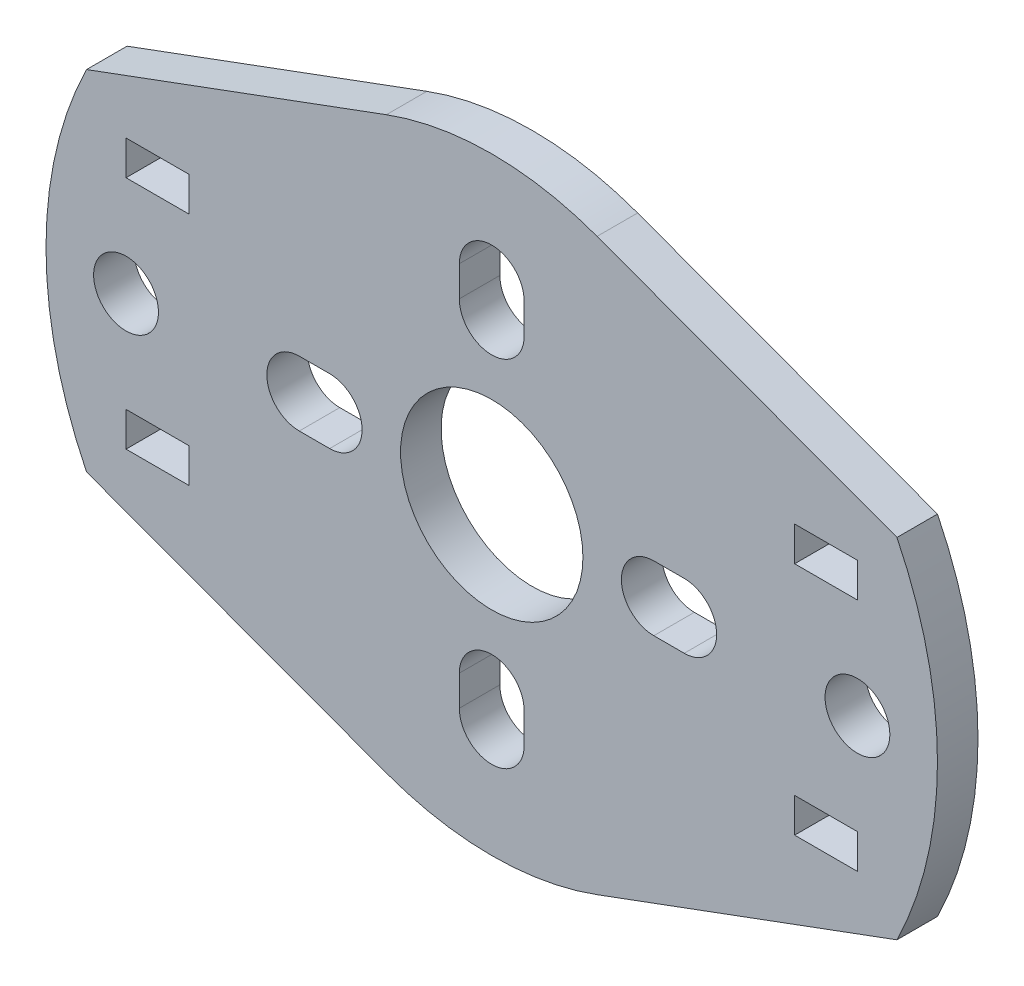
SolidWorks part; units mm, degrees
material "Thornel VCB-20 Carbon Cloth"
ref_plane "Front Plane" through (0, 0, 0) normal (0, 0, 1) x (1, 0, 0)
ref_plane "Top Plane" through (0, 0, 0) normal (0, 1, 0) x (1, 0, 0)
ref_plane "Right Plane" through (0, 0, 0) normal (1, 0, 0) x (0, 0, -1)
sketch "Sketch1" plane through (0, 0, 0) normal (0, 0, 1) x (1, 0, 0)
  line L0 (-105.2, 14.0698) -> (-120, 8.6)
  line L1 (-120, 8.6) -> (-120, -8.6)
  line L2 (-120, 0) -> (-80, 0) construction
  line L3 (-80, -8.6) -> (-80, 8.6)
  line L4 (-80, 8.6) -> (-94.8, 14.0698)
  line L5 (-80, -8.6) -> (-94.8, -14.0698)
  line L6 (-105.2, -14.0698) -> (-120, -8.6)
  line L15 (-114.95, 6.65) -> (-118.05, 6.65)
  line L16 (-118.05, 6.65) -> (-118.05, 4.95)
  line L17 (-118.05, 4.95) -> (-114.95, 4.95)
  line L18 (-114.95, 4.95) -> (-114.95, 6.65)
  line L19 (-114.95, 6.65) -> (-118.05, 6.65)
  line L20 (-118.05, 6.65) -> (-118.05, 4.95)
  line L21 (-118.05, 4.95) -> (-114.95, 4.95)
  line L22 (-114.95, 4.95) -> (-114.95, 6.65)
  line L27 (-81.95, 6.65) -> (-85.05, 6.65)
  line L28 (-85.05, 6.65) -> (-85.05, 4.95)
  line L29 (-85.05, 4.95) -> (-81.95, 4.95)
  line L30 (-81.95, 4.95) -> (-81.95, 6.65)
  line L31 (-81.95, 6.65) -> (-85.05, 6.65)
  line L32 (-85.05, 6.65) -> (-85.05, 4.95)
  line L33 (-85.05, 4.95) -> (-81.95, 4.95)
  line L34 (-81.95, 4.95) -> (-81.95, 6.65)
  line L39 (-114.95, -4.95) -> (-118.05, -4.95)
  line L40 (-118.05, -4.95) -> (-118.05, -6.65)
  line L41 (-118.05, -6.65) -> (-114.95, -6.65)
  line L42 (-114.95, -6.65) -> (-114.95, -4.95)
  line L43 (-114.95, -4.95) -> (-118.05, -4.95)
  line L44 (-118.05, -4.95) -> (-118.05, -6.65)
  line L45 (-118.05, -6.65) -> (-114.95, -6.65)
  line L46 (-114.95, -6.65) -> (-114.95, -4.95)
  line L51 (-81.95, -4.95) -> (-85.05, -4.95)
  line L52 (-85.05, -4.95) -> (-85.05, -6.65)
  line L53 (-85.05, -6.65) -> (-81.95, -6.65)
  line L54 (-81.95, -6.65) -> (-81.95, -4.95)
  line L55 (-81.95, -4.95) -> (-85.05, -4.95)
  line L56 (-85.05, -4.95) -> (-85.05, -6.65)
  line L57 (-85.05, -6.65) -> (-81.95, -6.65)
  line L58 (-81.95, -6.65) -> (-81.95, -4.95)
  circle A0 centre (-100, 0) radius 15 construction
  arc A1 (-105.2, -14.0698) -> (-94.8, -14.0698) centre (-100, 0) ccw
  arc A2 (-94.8, 14.0698) -> (-105.2, 14.0698) centre (-100, 0) ccw
  dimension "D1" = 2
  dimension "D2" = 2
  dimension "D3" = 2
  dimension "D4" = 0.05
  dimension "D5" = 0.05
  dimension "D6" = 0.05
  dimension "D7" = 0.05
extrude "Boss-Extrude1" add sketch "Sketch1" along normal blind 2
sketch "Sketch2" plane through (0, 0, 2) normal (0, 0, 1) x (1, 0, 0)
  line L0 (-108, 0) -> (-109.5, 0) construction
  line L1 (-108, -1.6) -> (-109.5, -1.6)
  line L2 (-108, 1.6) -> (-109.5, 1.6)
  line L4 (-100, 8) -> (-100, 9.5) construction
  line L5 (-101.6, 8) -> (-101.6, 9.5)
  line L6 (-98.4, 8) -> (-98.4, 9.5)
  line L7 (-92, 0) -> (-90.5, 0) construction
  line L8 (-92, 1.6) -> (-90.5, 1.6)
  line L9 (-92, -1.6) -> (-90.5, -1.6)
  line L10 (-100, -8) -> (-100, -9.5) construction
  line L11 (-98.4, -8) -> (-98.4, -9.5)
  line L12 (-101.6, -8) -> (-101.6, -9.5)
  circle A0 centre (-100, 0) radius 4.5
  arc A1 (-108, -1.6) -> (-108, 1.6) centre (-108, 0) ccw
  arc A2 (-109.5, 1.6) -> (-109.5, -1.6) centre (-109.5, 0) ccw
  arc A3 (-101.6, 8) -> (-98.4, 8) centre (-100, 8) ccw
  arc A4 (-98.4, 9.5) -> (-101.6, 9.5) centre (-100, 9.5) ccw
  arc A5 (-92, 1.6) -> (-92, -1.6) centre (-92, 0) ccw
  arc A6 (-90.5, -1.6) -> (-90.5, 1.6) centre (-90.5, 0) ccw
  arc A7 (-98.4, -8) -> (-101.6, -8) centre (-100, -8) ccw
  arc A8 (-101.6, -9.5) -> (-98.4, -9.5) centre (-100, -9.5) ccw
  point P5 (-108.75, 0)
  point P16 (-100, 8.75)
  point P23 (-91.25, 0)
  point P30 (-100, -8.75)
  point P35 (-100, 0)
  dimension "D2" = 9
  dimension "D4" = 16
  dimension "D5" = 19
  dimension "D6" = 3.2
  dimension "D3" = 4
extrude "Cut-Extrude1" cut sketch "Sketch2" against normal up to next
sketch "Sketch5" plane through (0, 0, 2) normal (0, 0, 1) x (1, 0, 0)
  line L0 (-120, 8.6) -> (-120, -8.6)
  line L1 (-80, 8.6) -> (-80, -8.6)
  arc A0 (-120, -8.6) -> (-120, 8.6) centre (-102.51, 0) cw
  arc A1 (-80, 8.6) -> (-80, -8.6) centre (-97.49, 0) cw
  point P5 (-122, 0)
  dimension "D1" = 2
extrude "Boss-Extrude2" add sketch "Sketch5" against normal up to vertex (2 mm away) up to point (-98.4, 8, 0)
sketch "Sketch3" plane through (0, 0, 2) normal (0, 0, 1) x (1, 0, 0)
  line L0 (-118.05, 4.95) -> (-118.05, -4.95) construction
  line L3 (-81.95, 4.95) -> (-81.95, -4.95) construction
  line L7 (-85.05, 4.95) -> (-81.95, 4.95) construction
  line L8 (-81.95, 4.95) -> (-81.95, 6.65) construction
  circle A0 centre (-118.05, 0) radius 1.6
  circle A1 centre (-81.95, 0) radius 1.6
  dimension "D1" = 3.2
extrude "Cut-Extrude2" cut sketch "Sketch3" against normal up to next
